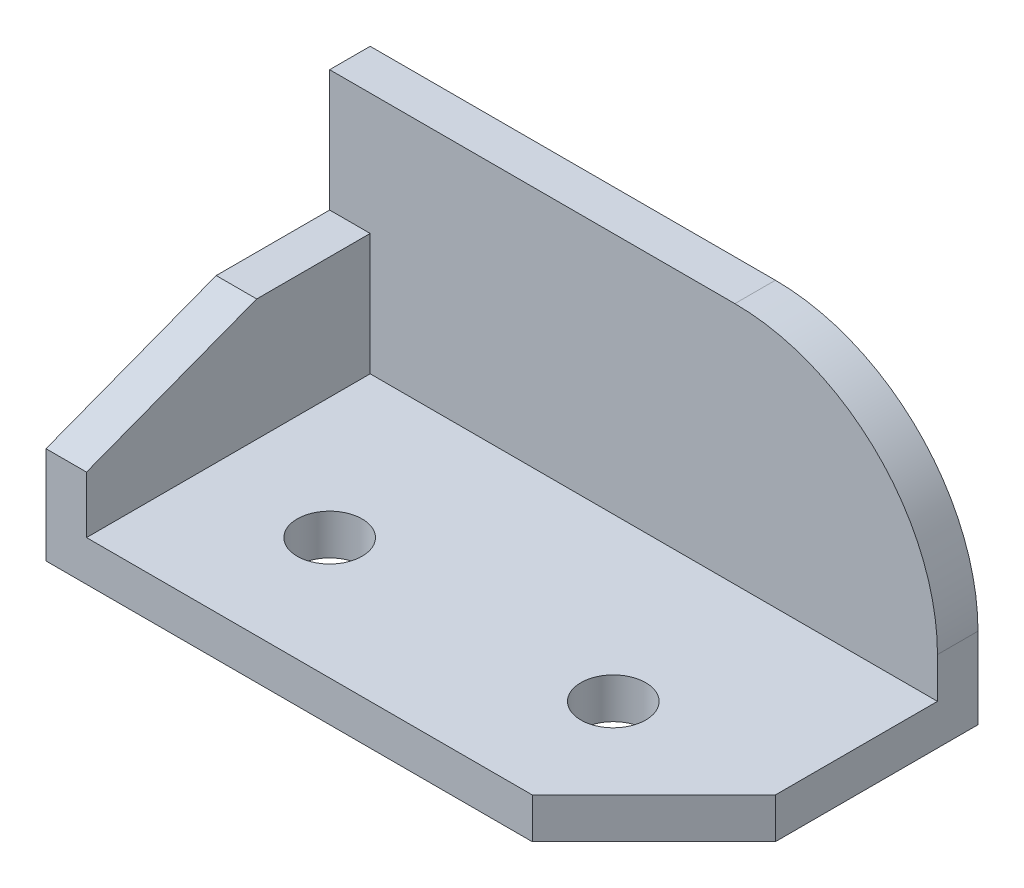
SolidWorks part; units mm, degrees
ref_plane "Front Plane" through (0, 0, 0) normal (0, 0, 1) x (1, 0, 0)
ref_plane "Top Plane" through (0, 0, 0) normal (0, 1, 0) x (1, 0, 0)
ref_plane "Right Plane" through (0, 0, 0) normal (1, 0, 0) x (0, 0, -1)
sketch "Sketch1" plane through (0, 0, 0) normal (0, 1, 0) x (1, 0, 0)
  line L0 (0, 0) -> (75, 0)
  line L1 (-55, 0) -> (55, 0) construction
  line L2 (75, 0) -> (75, -25)
  line L3 (75, -25) -> (60, -40)
  line L4 (60, -40) -> (0, -40)
  line L5 (0, -55) -> (0, 55) construction
  line L6 (0, -40) -> (0, 0)
  circle A0 centre (20, -25) radius 4
  circle A1 centre (55, -25) radius 4
  point P14 (0, 0)
  point P16 (0, 0)
  dimension "D5" = 8
  dimension "D6" = 8
  dimension "D1" = 60
  dimension "D2" = 75
  dimension "D3" = 25
  dimension "D4" = 40
  dimension "D7" = 35
  dimension "D8" = 55
  dimension "D9" = 15
extrude "Boss-Extrude1" add sketch "Sketch1" along normal blind 5
sketch "Sketch3" plane through (0, 0, 0) normal (1, 0, 0) x (0, 0, -1)
  line L0 (-40, 5) -> (-40, 12)
  line L1 (-40, 12) -> (-19, 20)
  line L2 (-19, 20) -> (0, 20)
  line L3 (0, 20) -> (0, 5)
  line L4 (-25, 5) -> (0, 5) construction
  line L5 (0, 5) -> (-40, 5)
  line L6 (22, 0) -> (-22, 0) construction
  dimension "D1" = 12
  dimension "D2" = 20
  dimension "D3" = 21
  dimension "D4" = 40
extrude "Boss-Extrude2" add sketch "Sketch3" along normal blind 5
sketch "Sketch4" plane through (0, 0, 0) normal (0, 0, 1) x (1, 0, 0)
  line L0 (0, 35) -> (0, 0)
  line L1 (0, -11) -> (0, 11) construction
  line L3 (0, 35) -> (50, 35)
  line L5 (0, 0) -> (75, 0)
  line L6 (22, 0) -> (-22, 0) construction
  line L8 (75, 10) -> (75, 0)
  line L9 (50, 35) -> (50, 10) construction
  line L10 (50, 10) -> (75, 10) construction
  arc A0 (50, 35) -> (75, 10) centre (50, 10) cw
  point P4 (0, 0)
  dimension "D1" = 25
  dimension "D2" = 35
  dimension "D3" = 75
extrude "Boss-Extrude3" add sketch "Sketch4" along normal blind 5
